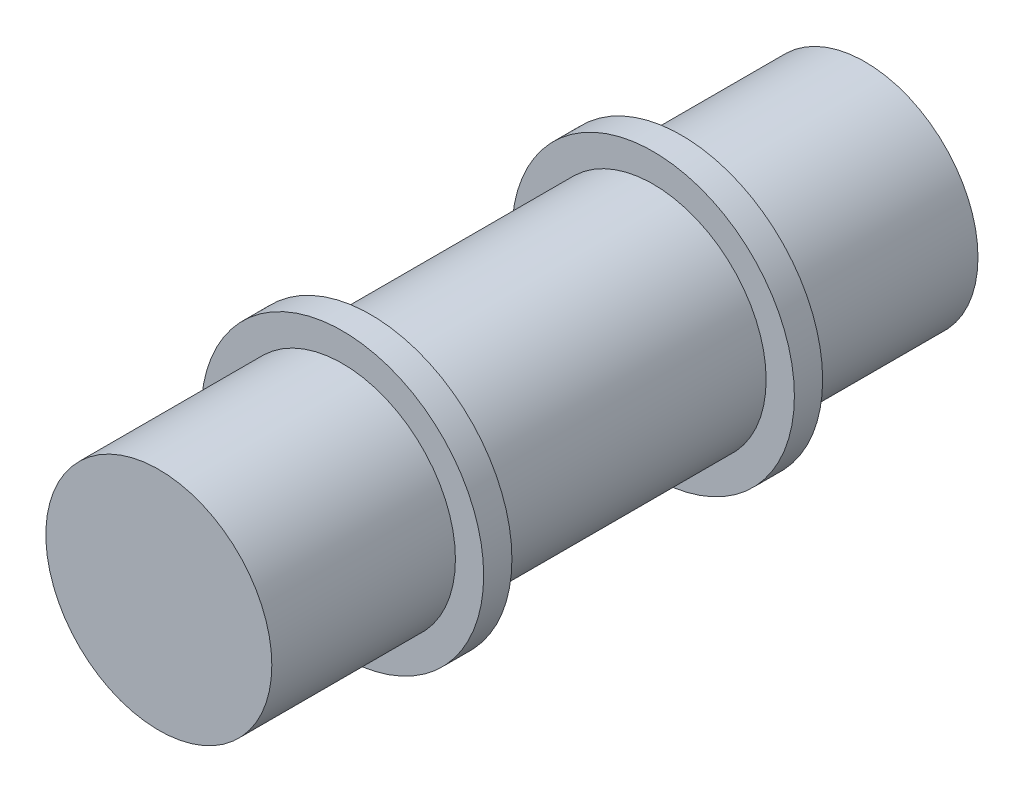
SolidWorks part; units mm, degrees
material "Beech"
ref_plane "Plan de face" through (0, 0, 0) normal (0, 0, 1) x (1, 0, 0)
ref_plane "Plan de dessus" through (0, 0, 0) normal (0, 1, 0) x (1, 0, 0)
ref_plane "Plan de droite" through (0, 0, 0) normal (1, 0, 0) x (0, 0, -1)
sketch "Sketch1" plane through (0, 0, 0) normal (0, 0, 1) x (1, 0, 0)
  circle A0 centre (0, 0) radius 10
  dimension "D1" = 20
extrude "Boss-Extrude1" add sketch "Sketch1" along normal blind 50
sketch "Sketch2" plane through (0, 0, 0) normal (1, 0, 0) x (0, 0, -1)
  line L0 (0, -10) -> (0, 10) construction
  line L1 (-50, 10) -> (-50, -10) construction
  line L2 (-50, -10) -> (0, -10) construction
  line L3 (0, 10) -> (-50, 10) construction
  line L4 (0, -10) -> (0, 10)
  line L5 (-50, 10) -> (-50, -10)
  line L6 (-50, -10) -> (0, -10)
  line L7 (0, 10) -> (-50, 10)
  line L8 (-25, 10) -> (-25, -10) construction
  line L9 (-35, 10) -> (-15, 10)
  line L10 (-35, 10) -> (-35, 8)
  line L11 (-35, 8) -> (-15, 8)
  line L12 (-15, 10) -> (-15, 8)
  line L13 (0, 10) -> (0, -10)
  line L14 (-50, 10) -> (-37, 10)
  line L15 (-50, 10) -> (-50, 8)
  line L16 (-50, 8) -> (-37, 8)
  line L17 (-37, 10) -> (-37, 8)
  line L18 (-13, 10) -> (-13, 8)
  line L19 (0, 8) -> (-13, 8)
  line L20 (-25, 0) -> (0, 0) construction
  point P10 (-25, 8)
  dimension "D1" = 20
  dimension "D2" = 2
  dimension "D3" = 2
revolve "Cut-Revolve1" cut sketch "Sketch2" angle 360 about L20
